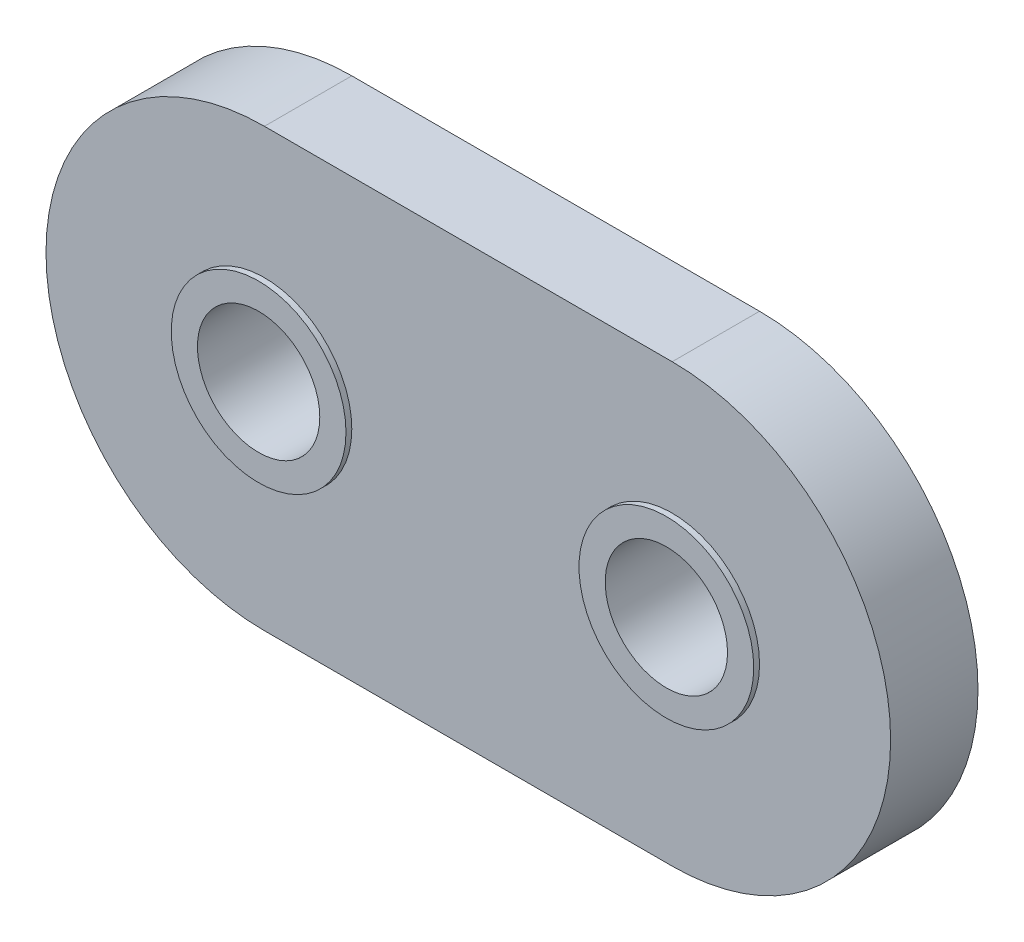
SolidWorks part; units mm, degrees
material "PLA"
ref_plane "前视基准面" through (0, 0, 0) normal (0, 0, 1) x (1, 0, 0)
ref_plane "上视基准面" through (0, 0, 0) normal (0, 1, 0) x (1, 0, 0)
ref_plane "右视基准面" through (0, 0, 0) normal (1, 0, 0) x (0, 0, -1)
sketch "草图1" plane through (0, 0, 0) normal (0, 0, 1) x (1, 0, 0)
  line L0 (0, 7.5) -> (14, 7.5)
  line L1 (0, -7.5) -> (14, -7.5)
  circle A0 centre (0, 0) radius 2.1
  circle A1 centre (14, 0) radius 2.1
  arc A2 (0, 7.5) -> (0, -7.5) centre (0, 0) ccw
  arc A3 (14, -7.5) -> (14, 7.5) centre (14, 0) ccw
  dimension "D2" = 4.2
  dimension "D3" = 15
  dimension "D1" = 14
extrude "凸台-拉伸1" add sketch "草图1" along normal blind 3
sketch "草图2" plane through (0, 0, 3) normal (0, 0, 1) x (1, 0, 0)
  circle A0 centre (14, 0) radius 2.1 construction
  circle A1 centre (0, 0) radius 2.1 construction
  circle A2 centre (14, 0) radius 2.1
  circle A3 centre (0, 0) radius 2.1
  circle A4 centre (0, 0) radius 3
  circle A5 centre (14, 0) radius 3
  dimension "D1" = 6
  dimension "D2" = 6
extrude "凸台-拉伸2" add sketch "草图2" along normal blind 0.2
